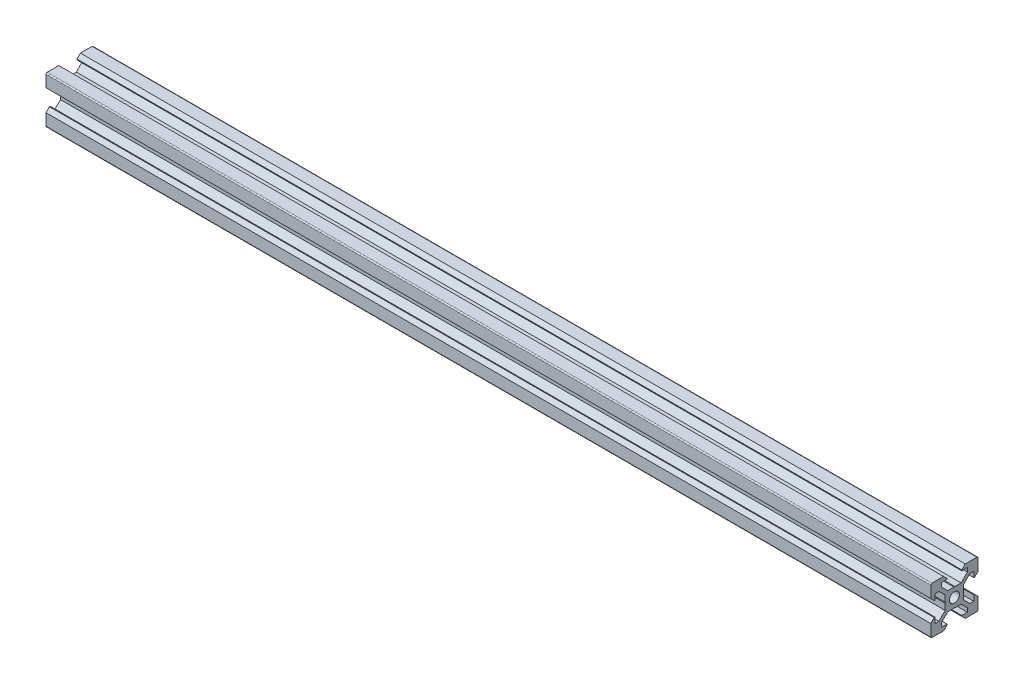
SolidWorks part; units mm, degrees
material "6061-T6 (SS)"
ref_plane "Top" through (0, 0, 0) normal (0, 0, 1) x (1, 0, 0)
ref_plane "Front" through (0, 0, 0) normal (0, 1, 0) x (1, 0, 0)
ref_plane "Right" through (0, 0, 0) normal (1, 0, 0) x (0, 0, -1)
sketch "Profile Sketch" plane through (0, 0, 0) normal (1, 0, 0) x (0, 0, -1)
  line L0 (-0.5, 10) -> (-5.42, 10)
  line L1 (-4.5, 8.2) -> (-4.5, 6.56)
  line L2 (-4.5, 6.56) -> (-7.16, 3.9)
  line L3 (-7.16, 3.9) -> (-9.79, 3.9)
  line L4 (-9.79, 3.9) -> (-10, 3.69)
  line L7 (-3.4387, 5.5) -> (-6.1, 2.8387)
  line L8 (-6.1, 2.8387) -> (-6.1, -0.21)
  line L9 (-6.875, 8.545) -> (-6.875, 8.2)
  line L10 (-6.875, 8.2) -> (-4.5, 8.2)
  line L11 (-6.875, 8.545) -> (-5.42, 10)
  line L12 (0, -10) -> (0, 10) construction
  line L13 (-20, 0) -> (20, 0) construction
  line L14 (-10, -10) -> (-10, 10) construction
  line L15 (-6.875, -8.545) -> (-5.42, -10)
  line L16 (-6.875, -8.2) -> (-4.5, -8.2)
  line L17 (-6.875, -8.545) -> (-6.875, -8.2)
  line L18 (-3.44, -5.5) -> (-6.1, -2.8387)
  line L21 (-7.16, -3.9) -> (-9.79, -3.9)
  line L22 (-4.5, -6.56) -> (-7.16, -3.9)
  line L23 (-4.5, -8.2) -> (-4.5, -6.56)
  line L24 (-0.5, -10) -> (-5.42, -10)
  line L25 (-10, 0) -> (-20, 10) construction
  line L26 (-18.545, 3.125) -> (-18.2, 3.125)
  line L27 (-13.125, -8.545) -> (-13.125, -8.2)
  line L28 (-13.125, -8.2) -> (-15.5, -8.2)
  line L29 (-13.125, -8.545) -> (-14.58, -10)
  line L30 (-15.5, -8.2) -> (-15.5, -6.56)
  line L31 (-15.5, -6.56) -> (-12.84, -3.9)
  line L32 (-12.84, -3.9) -> (-10.21, -3.9)
  line L33 (-20, 4.58) -> (-20, 9.5)
  line L34 (-13.9, 2.8387) -> (-13.9, 0.21)
  line L35 (-16.56, 5.5) -> (-13.9, 2.8387)
  line L36 (-12.84, 3.9) -> (-10.21, 3.9)
  line L37 (-15.5, 6.56) -> (-12.84, 3.9)
  line L38 (-15.5, 8.2) -> (-15.5, 6.56)
  line L39 (-13.125, 8.545) -> (-14.58, 10)
  line L40 (-13.125, 8.2) -> (-15.5, 8.2)
  line L41 (-13.125, 8.545) -> (-13.125, 8.2)
  line L42 (-18.2, 3.125) -> (-18.2, 5.5)
  line L43 (-18.545, 3.125) -> (-20, 4.58)
  line L44 (-18.2, 5.5) -> (-16.56, 5.5)
  line L45 (-14.58, 10) -> (-19.5, 10)
  line L46 (-16.56, -5.5) -> (-13.9, -2.8387)
  line L47 (-14.58, -10) -> (-19.5, -10)
  line L48 (-18.2, -5.5) -> (-16.56, -5.5)
  line L49 (-18.545, -3.125) -> (-20, -4.58)
  line L50 (-18.2, -3.125) -> (-18.2, -5.5)
  line L51 (-20, -4.58) -> (-20, -9.5)
  line L52 (-18.545, -3.125) -> (-18.2, -3.125)
  line L53 (10, -10) -> (10, 10) construction
  line L99 (-10, 3.69) -> (-10.21, 3.9)
  line L100 (-10, -3.69) -> (-10.21, -3.9)
  line L101 (-9.79, -3.9) -> (-10, -3.69)
  line L102 (-13.9, -0.21) -> (-13.69, 0)
  line L103 (-13.69, 0) -> (-13.9, 0.21)
  line L104 (-13.9, -0.21) -> (-13.9, -2.8387)
  line L105 (-6.1, -0.21) -> (-6.31, 0)
  line L106 (-6.31, 0) -> (-6.1, -0.21)
  line L107 (-6.1, -0.21) -> (-6.1, -2.8387)
  line L117 (-5.42, -10) -> (-0.5, -10)
  line L118 (20, -10) -> (20, 10) construction
  line L119 (20, -10) -> (-20, -10) construction
  line L120 (-20, -10) -> (-20, 10) construction
  line L121 (20, 10) -> (-20, 10) construction
  line L122 (20, -10) -> (-20, 10) construction
  line L123 (-20, -10) -> (20, 10) construction
  line L124 (-5.42, 10) -> (-0.5, 10)
  line L125 (-1.455, 3.125) -> (-1.8, 3.125)
  line L126 (-1.455, -3.125) -> (-1.8, -3.125)
  line L127 (-1.8, -5.5) -> (-3.44, -5.5)
  line L128 (-1.8, 5.5) -> (-3.44, 5.5)
  line L129 (-1.8, 3.125) -> (-1.8, 5.5)
  line L130 (-1.8, -3.125) -> (-1.8, -5.5)
  line L131 (0, -4.58) -> (0, -9.5)
  line L132 (0, 4.58) -> (0, 9.5)
  line L133 (-1.455, 3.125) -> (0, 4.58)
  line L134 (-1.455, -3.125) -> (0, -4.58)
  circle A0 centre (-10, 0) radius 2.1
  arc A1 (-19.5, 10) -> (-20, 9.5) centre (-19.5, 9.5) ccw
  arc A2 (-19.5, -10) -> (-20, -9.5) centre (-19.5, -9.5) cw
  arc A3 (-0.5, -10) -> (0, -9.5) centre (-0.5, -9.5) ccw
  arc A4 (-0.5, 10) -> (0, 9.5) centre (-0.5, 9.5) cw
  point P2 (-17.38, 5.5)
  point P35 (-2.4957, 0)
  point P76 (-2.62, 5.5)
  point P108 (0, -8.2)
  point P119 (0, 8.2)
  point P131 (0, 0)
  point P143 (0, 0)
  dimension "D4" = 5.42
  dimension "D5" = 40
  dimension "D6" = 4.2
  dimension "D16" = 0.5
  dimension "D1" = 0.21
  dimension "D2" = 45
  dimension "D3" = 20
  dimension "D7" = 1.5
  dimension "D8" = 1.8
  dimension "D9" = 10
  dimension "D10" = 3.9
  dimension "D11" = 3.9
  dimension "D13" = 3.125
  dimension "D14" = 5.5
  dimension "D15" = 1.64
extrude "Profile Extrude" add sketch "Profile Sketch" along normal blind 375
equation "\"M8x1.25_Close_Hole\"= 8.4"
